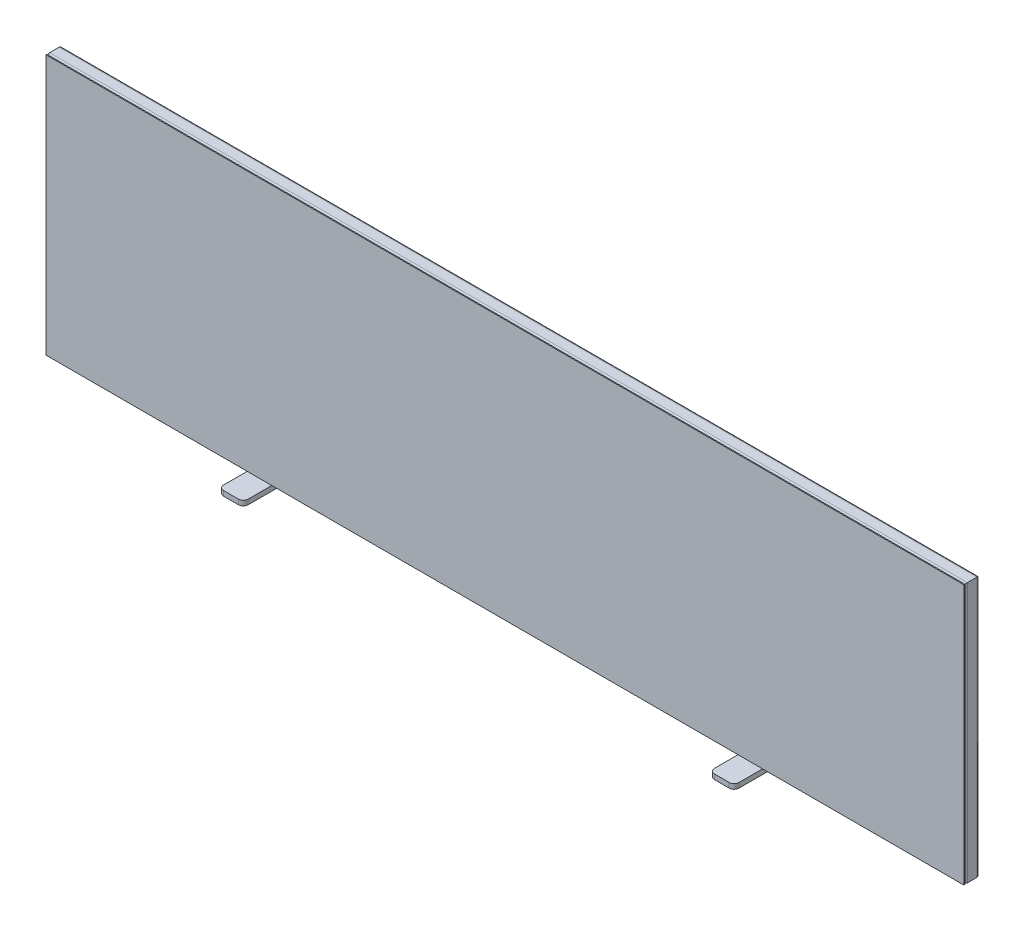
SolidWorks part; units mm, degrees
material "Q235A"
ref_plane "前视" through (0, 0, 0) normal (0, 0, 1) x (1, 0, 0)
ref_plane "上视" through (0, 0, 0) normal (0, 1, 0) x (1, 0, 0)
ref_plane "右视" through (0, 0, 0) normal (1, 0, 0) x (0, 0, -1)
sketch "草图1" plane through (0, 0, 0) normal (0, 0, 1) x (1, 0, 0)
  line L1 (920, -250) -> (-920, -250)
  line L2 (920, -250) -> (920, 250)
  line L3 (920, 250) -> (-920, 250)
  line L4 (-920, -250) -> (-920, 250)
  line L5 (920, -250) -> (-920, 250) construction
  line L6 (920, 250) -> (-920, -250) construction
  point P0 (0, 0)
  dimension "D1" = 500
  dimension "D2" = 1840
other "结构构件1"
ref_plane "基准面1" through (-920, -250, 0) normal (0, 1, 0) x (-1, 0, 0)
sketch "Sketch1" plane through (-920, -250, 0) normal (0, 1, 0) x (-1, 0, 0)
  line L0 (-9.8, -12.5) -> (9.8, -12.5)
  line L1 (-12.5, -9.8) -> (-12.5, 9.8)
  line L2 (9.8, 12.5) -> (-9.8, 12.5)
  line L3 (12.5, 9.8) -> (12.5, -9.8)
  line L4 (-9.8, -15) -> (9.8, -15)
  line L5 (-15, -9.8) -> (-15, 9.8)
  line L6 (9.8, 15) -> (-9.8, 15)
  line L7 (15, 9.8) -> (15, -9.8)
  arc A0 (15, 9.8) -> (9.8, 15) centre (9.8, 9.8) ccw
  arc A1 (9.8, -15) -> (15, -9.8) centre (9.8, -9.8) ccw
  arc A2 (-15, -9.8) -> (-9.8, -15) centre (-9.8, -9.8) ccw
  arc A3 (-9.8, 15) -> (-15, 9.8) centre (-9.8, 9.8) ccw
  arc A4 (-9.8, 12.5) -> (-12.5, 9.8) centre (-9.8, 9.8) ccw
  arc A5 (12.5, 9.8) -> (9.8, 12.5) centre (9.8, 9.8) ccw
  arc A6 (9.8, -12.5) -> (12.5, -9.8) centre (9.8, -9.8) ccw
  arc A7 (-12.5, -9.8) -> (-9.8, -12.5) centre (-9.8, -9.8) ccw
  point P0 (0, 15)
  point P1 (15, 0)
  point P2 (0, -15)
  point P3 (-15, 0)
  point P4 (-15, 15)
  point P5 (15, 15)
  point P6 (15, -15)
  point P7 (-15, -15)
  point P8 (0, 0)
  point P33 (0, 0)
  dimension "D1" = 5.2
  dimension "Thickness" = 2.5
  dimension "V_leg" = 30
  dimension "H_leg" = 30
sketch "草图3" plane through (0, 0, 15) normal (0, 0, 1) x (1, 0, 0)
  line L1 (-935, 265) -> (935, 265)
  line L2 (-935, 265) -> (-935, -265)
  line L3 (-935, -265) -> (935, -265)
  line L4 (935, 265) -> (935, -265)
extrude "凸台-拉伸1" add sketch "草图3" along normal blind 2 separate body
sketch "草图4" plane through (0, -265, 0) normal (0, -1, 0) x (1, 0, 0)
  line L0 (920, 0) -> (-920, 0) construction
  line L1 (-475, -75) -> (-525, -75)
  line L2 (-475, -75) -> (-475, 75)
  line L3 (-475, 75) -> (-525, 75)
  line L4 (-525, -75) -> (-525, 75)
  line L5 (-475, -75) -> (-525, 75) construction
  line L6 (-475, 75) -> (-525, -75) construction
  line L7 (0, -50) -> (0, 50) construction
  point P0 (-500, 0)
  dimension "D1" = 50
  dimension "D2" = 150
  dimension "D3" = 500
extrude "凸台-拉伸2" add sketch "草图4" along normal blind 10 separate body
pattern_linear "阵列(线性)1" count 2 spacing 1000 along (1, 0, 0) of "凸台-拉伸2"
fillet "圆角1" radius 10 4 edges at (-475, -270, -75) (-525, -270, -75) (-475, -270, 75) (-525, -270, 75)
fillet "圆角2" radius 10 4 edges at (525, -270, 75) (525, -270, -75) (475, -270, -75) (475, -270, 75)
